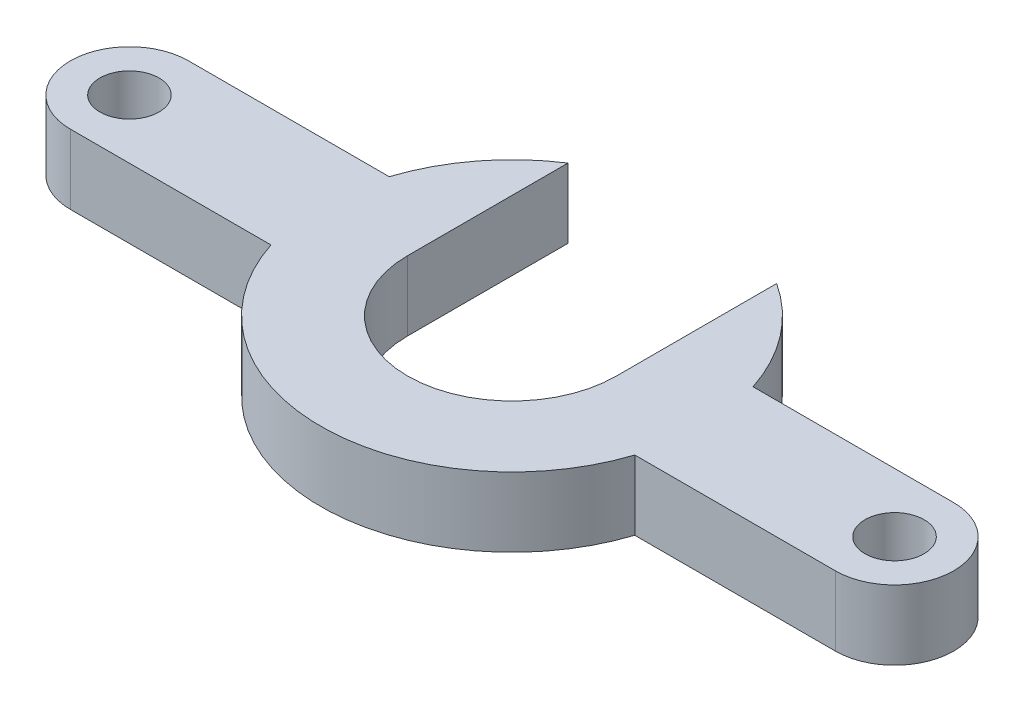
SolidWorks part; units mm, degrees
ref_plane "Front Plane" through (0, 0, 0) normal (0, 0, 1) x (1, 0, 0)
ref_plane "Top Plane" through (0, 0, 0) normal (0, 1, 0) x (1, 0, 0)
ref_plane "Right Plane" through (0, 0, 0) normal (1, 0, 0) x (0, 0, -1)
sketch "Sketch1" plane through (0, 0, 0) normal (0, 1, 0) x (1, 0, 0)
  line L0 (-55, 0) -> (55, 0) construction
  line L1 (55, 8.5) -> (26.1534, 8.5)
  line L2 (63.5, 0) -> (63.5, -8.5) construction
  line L3 (55, -8.5) -> (26.1534, -8.5)
  line L4 (-63.5, 0) -> (-63.5, -8.5) construction
  line L5 (-55, 0) -> (63.5, 0) construction
  line L6 (55, 0) -> (-63.5, 0) construction
  line L7 (-15, 0) -> (-15, 23.0489)
  line L8 (15, 0) -> (15, 23.0489)
  line L9 (-15, 8.5) -> (15, 8.5) construction
  line L10 (26.1534, 8.5) -> (15, 8.5) construction
  line L11 (-26.1534, 8.5) -> (-15, 8.5) construction
  line L12 (15, 8.5) -> (26.1534, 8.5) construction
  line L13 (-26.1534, -8.5) -> (26.1534, -8.5) construction
  line L14 (26.1534, -8.5) -> (12.3592, -8.5) construction
  line L15 (12.3592, 8.5) -> (-12.3592, 8.5) construction
  line L16 (-12.3592, 8.5) -> (-15, 8.5) construction
  line L17 (12.3592, 8.5) -> (-12.3592, 8.5) construction
  line L18 (-12.3592, 8.5) -> (-15, 8.5) construction
  line L19 (-15, 8.5) -> (-26.1534, 8.5) construction
  line L20 (-15, 8.5) -> (-26.1534, 8.5) construction
  line L21 (-26.1534, 8.5) -> (-55, 8.5)
  line L22 (15, 8.5) -> (12.3592, 8.5) construction
  line L23 (15, 8.5) -> (12.3592, 8.5) construction
  line L24 (26.1534, 8.5) -> (15, 8.5) construction
  line L25 (-12.3592, -8.5) -> (-26.1534, -8.5) construction
  line L26 (-26.1534, -8.5) -> (-55, -8.5)
  line L27 (-12.3592, -8.5) -> (-26.1534, -8.5) construction
  line L28 (12.3592, -8.5) -> (-12.3592, -8.5) construction
  line L29 (12.3592, -8.5) -> (-12.3592, -8.5) construction
  line L30 (26.1534, -8.5) -> (12.3592, -8.5) construction
  line L31 (63.5, 8.5) -> (55, 8.5) construction
  line L32 (63.5, 8.5) -> (63.5, 0) construction
  line L33 (63.5, -8.5) -> (55, -8.5) construction
  line L34 (-55, 8.5) -> (-63.5, 8.5) construction
  line L35 (-63.5, 8.5) -> (-63.5, 0) construction
  line L36 (-55, -8.5) -> (-63.5, -8.5) construction
  arc A0 (-15, 23.0489) -> (-26.1534, 8.5) centre (0, 0) ccw
  arc A1 (-15, 0) -> (15, 0) centre (0, 0) ccw
  circle A2 centre (-55, 0) radius 4.25
  circle A3 centre (55, 0) radius 4.25
  arc A4 (15, 23.0489) -> (-15, 23.0489) centre (0, 0) ccw construction
  arc A5 (15, 0) -> (-15, 0) centre (0, 0) ccw construction
  arc A6 (27.5, 0) -> (26.1534, 8.5) centre (0, 0) ccw construction
  arc A7 (26.1534, 8.5) -> (15, 23.0489) centre (0, 0) ccw
  arc A8 (26.1534, -8.5) -> (27.5, 0) centre (0, 0) ccw construction
  arc A9 (-26.1534, 8.5) -> (-27.5, 0) centre (0, 0) ccw construction
  arc A10 (-26.1534, -8.5) -> (26.1534, -8.5) centre (0, 0) ccw
  arc A11 (-27.5, 0) -> (-26.1534, -8.5) centre (0, 0) ccw construction
  arc A12 (-55, -8.5) -> (-55, 8.5) centre (-55, 0) cw
  arc A13 (55, 8.5) -> (55, -8.5) centre (55, 0) cw
  dimension "D1" = 55
  dimension "D2" = 30
  dimension "D4" = 8.5
  dimension "D3" = 55
  dimension "D5" = 8.5
  dimension "D6" = 17
extrude "Boss-Extrude1" add sketch "Sketch1" along normal blind 10
